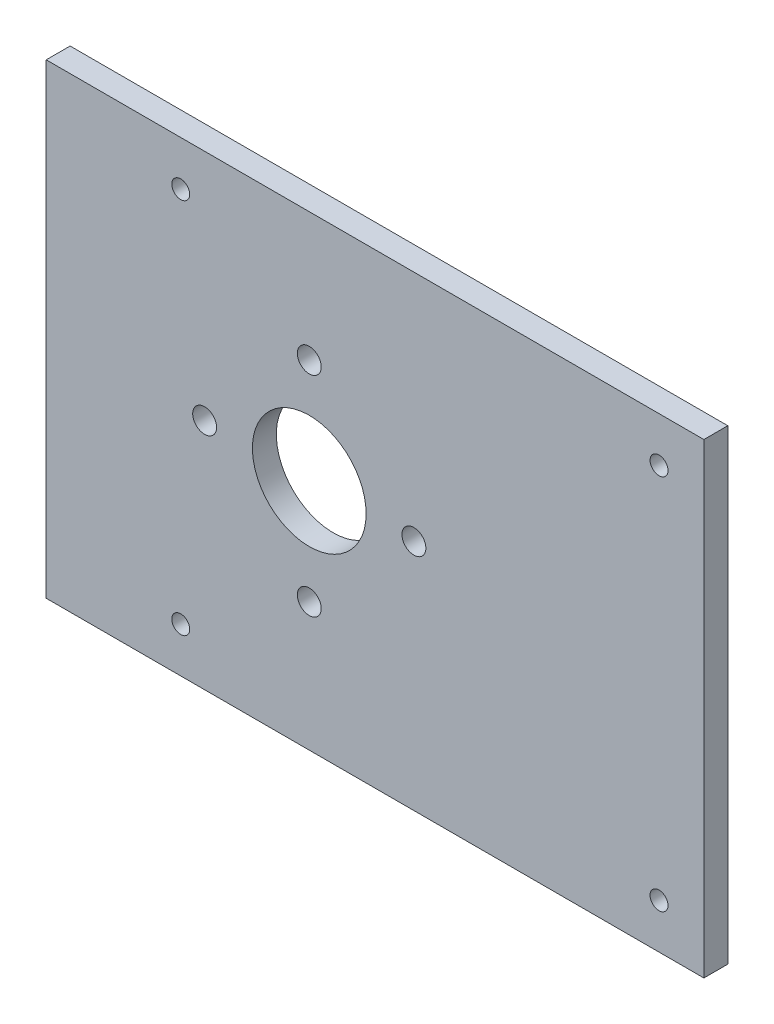
SolidWorks part; units mm, degrees
material "A-玻璃纤维"
ref_plane "前视基准面" through (0, 0, 0) normal (0, 0, 1) x (1, 0, 0)
ref_plane "上视基准面" through (0, 0, 0) normal (0, 1, 0) x (1, 0, 0)
ref_plane "右视基准面" through (0, 0, 0) normal (1, 0, 0) x (0, 0, -1)
sketch "草图1" plane through (0, 0, 0) normal (0, 0, 1) x (1, 0, 0)
  line L1 (-55, 39) -> (55, 39)
  line L2 (-55, 39) -> (-55, -39)
  line L3 (-55, -39) -> (55, -39)
  line L4 (55, 39) -> (55, -39)
  line L5 (-55, 39) -> (55, -39) construction
  line L6 (-55, -39) -> (55, 39) construction
  line L7 (-32.5, 31.5) -> (47.5, 31.5) construction
  line L8 (-32.5, 31.5) -> (-32.5, -31.5) construction
  line L9 (-32.5, -31.5) -> (47.5, -31.5) construction
  line L10 (47.5, 31.5) -> (47.5, -31.5) construction
  circle A0 centre (-32.5, 31.5) radius 1.5
  circle A1 centre (47.5, 31.5) radius 1.5
  circle A2 centre (47.5, -31.5) radius 1.5
  circle A3 centre (-32.5, -31.5) radius 1.5
  point P0 (0, 0)
  point P6 (0, 0)
  point P15 (0, 0)
  point P16 (0, 0)
  point P18 (47.5, 0)
  dimension "D5" = 3
  dimension "D1" = 110
  dimension "D2" = 78
  dimension "D3" = 7.5
  dimension "D4" = 80
  dimension "D6" = 102.5
extrude "凸台-拉伸1" add sketch "草图1" along normal blind 4
sketch "草图4" plane through (0, 0, 4) normal (0, 0, 1) x (1, 0, 0)
  line L0 (-11, -39) -> (-11, 39) construction
  line L1 (-55, -39) -> (55, -39) construction
  line L2 (55, 39) -> (-55, 39) construction
  line L3 (55, -39) -> (55, 39) construction
  circle A2 centre (-11, 0) radius 17.5 construction
  circle A3 centre (-11, 17.5) radius 2
  circle A4 centre (-28.5, 0) radius 2
  circle A5 centre (-11, -17.5) radius 2
  circle A6 centre (6.5, 0) radius 2
  circle A7 centre (-11, 0) radius 9.51
  dimension "D1" = 35
  dimension "D2" = 4
  dimension "D3" = 19.02
  dimension "D4" = 66
  dimension "D5" = 39
extrude "切除-拉伸1" cut sketch "草图4" against normal through all
